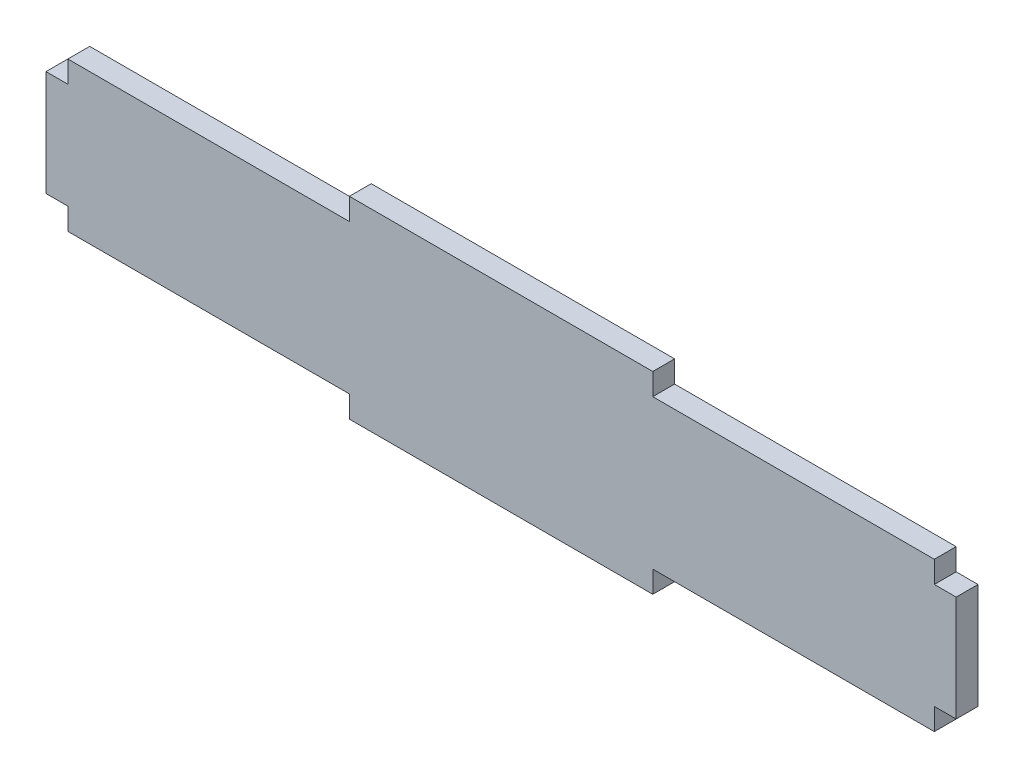
SolidWorks part; units mm, degrees
ref_plane "Front Plane" through (0, 0, 0) normal (0, 0, 1) x (1, 0, 0)
ref_plane "Top Plane" through (0, 0, 0) normal (0, 1, 0) x (1, 0, 0)
ref_plane "Right Plane" through (0, 0, 0) normal (1, 0, 0) x (0, 0, -1)
sketch "Sketch1" plane through (0, 0, 0) normal (0, 0, 1) x (1, 0, 0)
  line L1 (0, 0) -> (500, 0)
  line L2 (0, 0) -> (0, 106.02)
  line L3 (0, 106.02) -> (500, 106.02)
  line L4 (500, 0) -> (500, 106.02)
  dimension "D1" = 500
  dimension "D2" = 106.02
extrude "Boss-Extrude1" add sketch "Sketch1" along normal blind 12
sketch "Sketch2" plane through (0, 0, 12) normal (0, 0, 1) x (1, 0, 0)
  line L1 (500, 0) -> (488, 0)
  line L2 (500, 0) -> (500, 24)
  line L3 (500, 24) -> (488, 24)
  line L4 (488, 0) -> (488, 24)
  line L5 (500, 106.02) -> (488, 106.02)
  line L6 (500, 106.02) -> (500, 82.02)
  line L7 (500, 82.02) -> (488, 82.02)
  line L8 (488, 106.02) -> (488, 82.02)
  line L9 (0, 106.02) -> (12, 106.02)
  line L10 (0, 106.02) -> (0, 82.02)
  line L11 (0, 82.02) -> (12, 82.02)
  line L12 (12, 106.02) -> (12, 82.02)
  line L13 (0, 0) -> (12, 0)
  line L14 (0, 0) -> (0, 24)
  line L15 (0, 24) -> (12, 24)
  line L16 (12, 0) -> (12, 24)
  dimension "D1" = 24
  dimension "D2" = 12
extrude "Cut-Extrude1" cut sketch "Sketch2" against normal through all
sketch "Sketch3" plane through (0, 0, 12) normal (0, 0, 1) x (1, 0, 0)
  line L1 (12, 0) -> (166.6667, 0)
  line L2 (12, 0) -> (12, 12)
  line L3 (12, 12) -> (166.6667, 12)
  line L4 (166.6667, 0) -> (166.6667, 12)
  line L5 (488, 0) -> (333.3333, 0)
  line L6 (488, 0) -> (488, 12)
  line L7 (488, 12) -> (333.3333, 12)
  line L8 (333.3333, 0) -> (333.3333, 12)
  line L9 (12, 106.02) -> (166.6667, 106.02)
  line L10 (12, 106.02) -> (12, 94.02)
  line L11 (12, 94.02) -> (166.6667, 94.02)
  line L12 (166.6667, 106.02) -> (166.6667, 94.02)
  line L13 (488, 106.02) -> (333.3333, 106.02)
  line L14 (488, 106.02) -> (488, 94.02)
  line L15 (488, 94.02) -> (333.3333, 94.02)
  line L16 (333.3333, 106.02) -> (333.3333, 94.02)
  dimension "D1" = 12
  dimension "D2" = 166.6667
  dimension "D3" = 166.6667
extrude "Cut-Extrude2" cut sketch "Sketch3" against normal through all
scale "Scale1" scale about centroid uniform scaling yes scale factor 0.5
